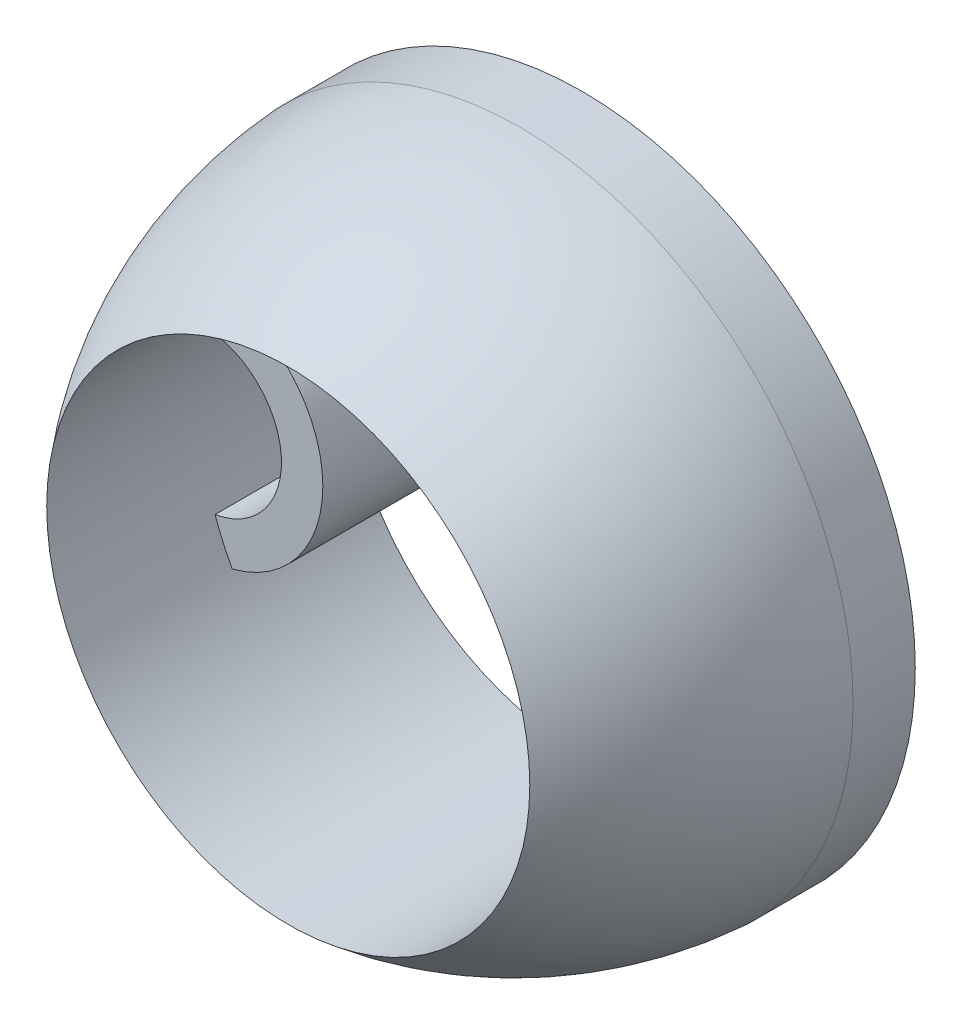
SolidWorks part; units mm, degrees
material "PLA (100% Honeyvone infill)"
ref_plane "Front Plane" through (0, 0, 0) normal (0, 0, 1) x (1, 0, 0)
ref_plane "Top Plane" through (0, 0, 0) normal (0, 1, 0) x (1, 0, 0)
ref_plane "Right Plane" through (0, 0, 0) normal (1, 0, 0) x (0, 0, -1)
sketch "Sketch1" plane through (0, 0, 0) normal (0, 1, 0) x (1, 0, 0)
  line L6 (-8.7415, 3.3896) -> (-8.7415, -0.4272)
  line L8 (11.7055, 3.3896) -> (11.7055, -23.2943)
  line L9 (11.7055, 3.3896) -> (-8.7415, 3.3896)
  arc A1 (-8.7415, -0.4272) -> (11.7055, -23.2943) centre (16.0035, 1.1239) ccw
  dimension "D1" = 3.8168
  dimension "D2" = 20.447
revolve "Revolve1" add sketch "Sketch1" angle 360 about L8
sketch "Sketch4" plane through (0, 0, -3.3896) normal (0, 0, -1) x (-1, 0, 0)
  circle A0 centre (-11.7055, 0) radius 14.8273
  dimension "D1" = 29.6545
extrude "Cut-Extrude2" cut sketch "Sketch4" against normal through all
sketch "Sketch5" plane through (0, 0, -3.3896) normal (0, 0, -1) x (-1, 0, 0)
  arc A0 (1.3708, 6.9899) -> (1.3708, -6.9899) centre (3.1218, 0) ccw
  circle A1 centre (-11.7055, 0) radius 14.8273 construction
  arc A3 (1.3708, -6.9899) -> (1.3708, 6.9899) centre (-11.7055, 0) ccw
  arc A4 (2.3204, 4.8084) -> (2.3204, -4.8084) centre (3.1218, 0) ccw
extrude "Extrude-Thin1" add sketch "Sketch5" against normal blind 8.509 thin contours A4
sketch "Sketch6" plane through (0, 0, 5.1194) normal (0, 0, 1) x (1, 0, 0)
